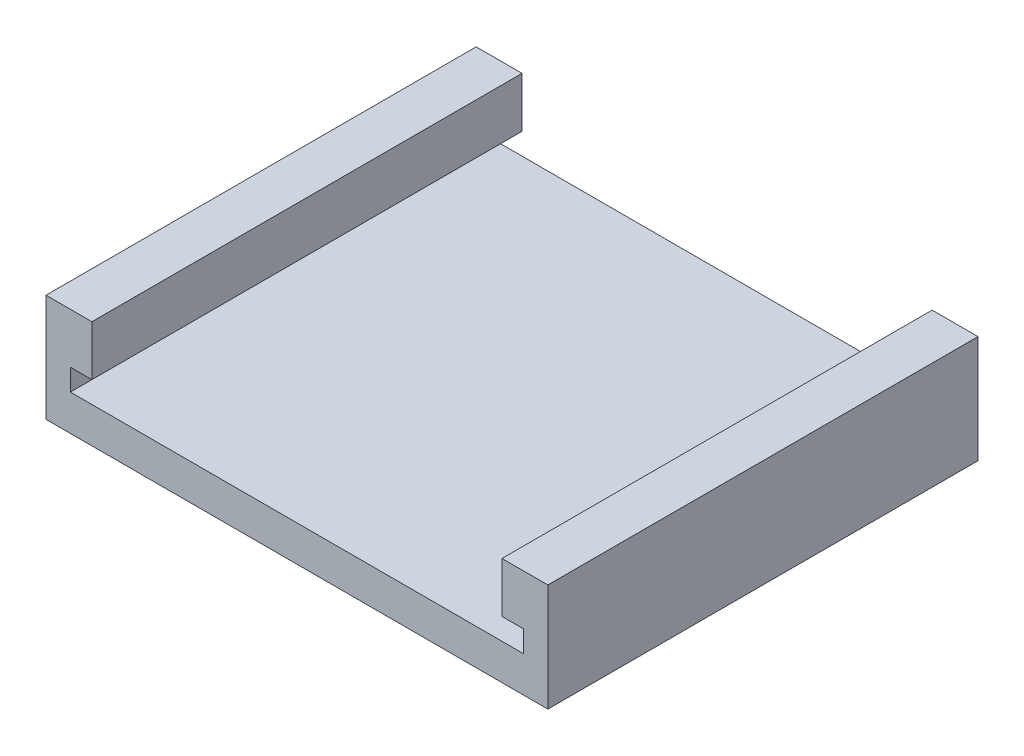
SolidWorks part; units mm, degrees
ref_plane "Front Plane" through (0, 0, 0) normal (0, 0, 1) x (1, 0, 0)
ref_plane "Top Plane" through (0, 0, 0) normal (0, 1, 0) x (1, 0, 0)
ref_plane "Right Plane" through (0, 0, 0) normal (1, 0, 0) x (0, 0, -1)
sketch "Sketch1" plane through (0, 0, 0) normal (0, 1, 0) x (1, 0, 0)
  line L1 (35, -30) -> (-35, -30)
  line L2 (35, -30) -> (35, 30)
  line L3 (35, 30) -> (-35, 30)
  line L4 (-35, -30) -> (-35, 30)
  line L5 (35, -30) -> (-35, 30) construction
  line L6 (35, 30) -> (-35, -30) construction
  point P0 (0, 0)
  dimension "D1" = 60
  dimension "D2" = 70
extrude "Boss-Extrude1" add sketch "Sketch1" along normal blind 5
sketch "Sketch2" plane through (0, 5, 0) normal (0, 1, 0) x (1, 0, 0)
  line L12 (-35, -30) -> (35, -30) construction
  line L21 (-35, 30) -> (-31.6, 30)
  line L22 (-35, 30) -> (-35, -30)
  line L23 (-35, -30) -> (-31.6, -30)
  line L24 (-31.6, 30) -> (-31.6, -30)
  line L26 (35, 30) -> (31.6, 30)
  line L27 (35, 30) -> (35, -30)
  line L28 (35, -30) -> (31.6, -30)
  line L29 (31.6, 30) -> (31.6, -30)
  point P0 (0, 0)
  dimension "D1" = 3.4
  dimension "D2" = 3.4
  dimension "D3" = 63.2
extrude "Boss-Extrude2" add sketch "Sketch2" along normal blind 10
sketch "Sketch5" plane through (-31.6, 0, 0) normal (1, 0, 0) x (0, 0, -1)
  line L0 (30, 15) -> (30, 0) construction
  line L1 (-30, 15) -> (30, 15)
  line L2 (-30, 15) -> (-30, 8)
  line L3 (-30, 8) -> (30, 8)
  line L4 (30, 15) -> (30, 8)
  dimension "D1" = 7
extrude "Boss-Extrude5" add sketch "Sketch5" along normal blind 3
sketch "Sketch6" plane through (31.6, 0, 0) normal (-1, 0, 0) x (0, 0, 1)
  line L0 (30, 15) -> (30, 0) construction
  line L1 (-30, 15) -> (30, 15)
  line L2 (-30, 15) -> (-30, 8)
  line L3 (-30, 8) -> (30, 8)
  line L4 (30, 15) -> (30, 8)
  dimension "D1" = 7
extrude "Boss-Extrude6" add sketch "Sketch6" along normal blind 3
